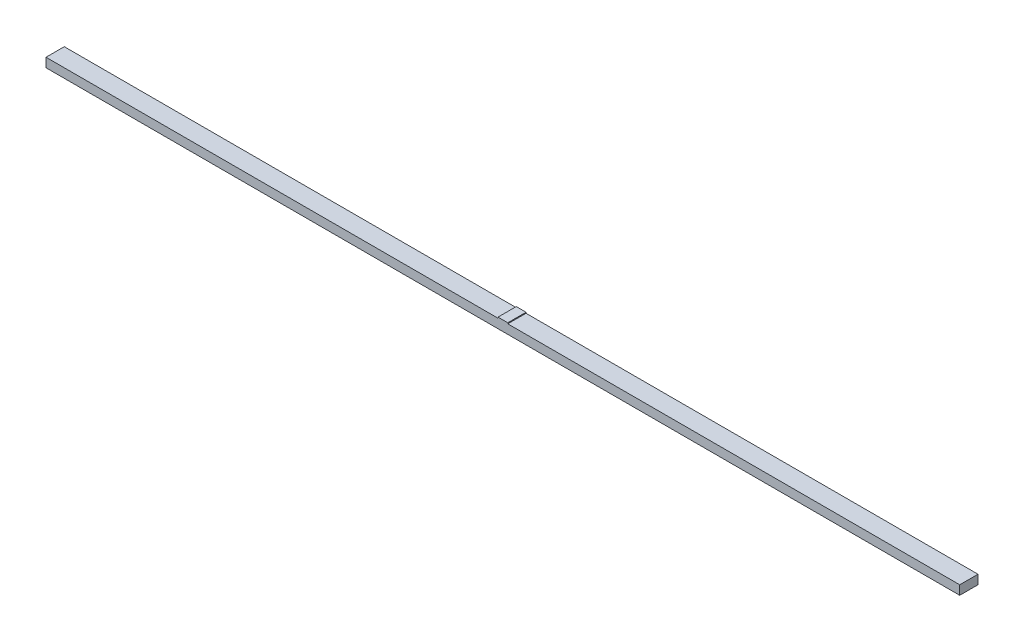
SolidWorks part; units mm, degrees
other "Static 1"
material "1023 Carbon Steel Sheet (SS)"
ref_plane "Front Plane" through (0, 0, 0) normal (0, 0, 1) x (1, 0, 0)
ref_plane "Top Plane" through (0, 0, 0) normal (0, 1, 0) x (1, 0, 0)
ref_plane "Right Plane" through (0, 0, 0) normal (1, 0, 0) x (0, 0, -1)
sketch "Sketch2" plane through (0, 0, 0) normal (0, 0, 1) x (1, 0, 0)
  line L0 (500, 0) -> (-500, 0)
  line L2 (0, 0) -> (0, 19.3194) construction
  dimension "D1" = 500
extrude "Extrude-Thin1" add sketch "Sketch2" along normal blind 20 thin
sketch "Sketch4" plane through (0, 10, 0) normal (0, 1, 0) x (1, 0, 0)
  line L0 (0, 0) -> (0, -66.977) construction
  line L1 (5.3626, -20) -> (-5.3626, -20)
  line L2 (500, -20) -> (-500, -20) construction
  line L3 (-5.3626, -20) -> (-5.3626, 0)
  line L4 (500, 0) -> (-500, 0) construction
  line L5 (-5.3626, 0) -> (5.3626, 0)
  line L7 (5.3626, -20) -> (5.3626, 0)
  point P11 (0, -20)
extrude "Boss-Extrude1" add sketch "Sketch4" along normal blind 1
